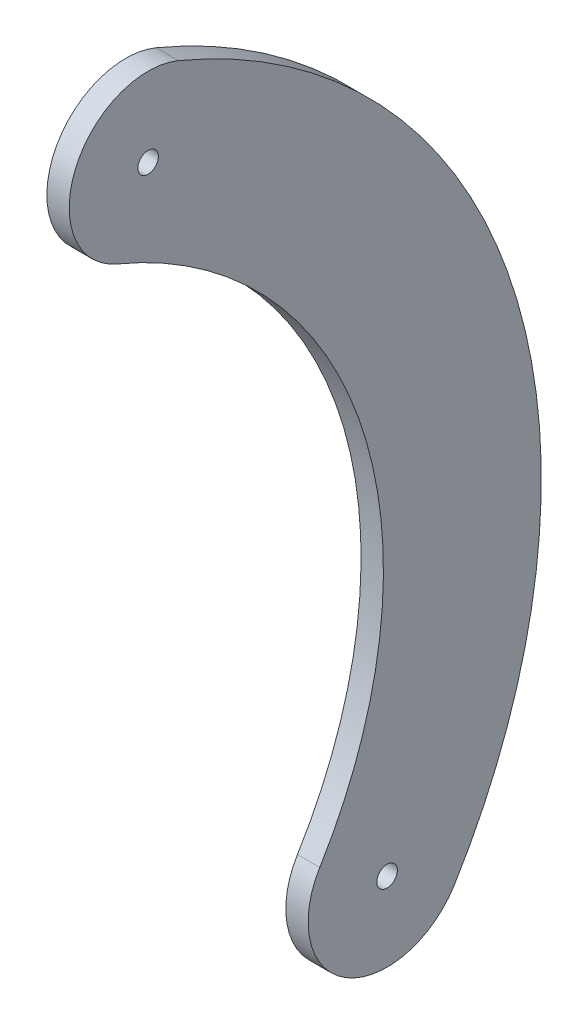
SolidWorks part; units mm, degrees
ref_plane "Front Plane" through (0, 0, 0) normal (0, 0, 1) x (1, 0, 0)
ref_plane "Top Plane" through (0, 0, 0) normal (0, 1, 0) x (1, 0, 0)
ref_plane "Right Plane" through (0, 0, 0) normal (1, 0, 0) x (0, 0, -1)
sketch "Sketch1" plane through (0, 0, 0) normal (1, 0, 0) x (0, 0, -1)
  line L0 (-85.3632, 0) -> (85.3632, 0) construction
  line L1 (0, 89.2233) -> (0, -89.2233) construction
  line L2 (-30.2742, 93.4694) -> (30.2742, -93.4694) construction
  line L3 (-11.2473, 99.6321) -> (49.301, -87.3068) construction
  line L4 (-49.301, 87.3068) -> (11.2473, -99.6321) construction
  line L5 (43.5935, 14.1196) -> (-43.5935, -14.1196) construction
  arc A0 (-11.2473, 99.6321) -> (-49.301, 87.3068) centre (-30.2742, 93.4694) ccw construction
  arc A1 (11.2473, -99.6321) -> (49.301, -87.3068) centre (30.2742, -93.4694) ccw construction
  circle A2 centre (-30.2742, 93.4694) radius 2.6067
  circle A3 centre (30.2742, -93.4694) radius 2.6067
  circle A4 centre (-30.2742, 93.4694) radius 20 construction
  circle A5 centre (30.2742, -93.4694) radius 20 construction
  arc A6 (-30.2742, 93.4694) -> (30.2742, -93.4694) centre (-79.9123, -25.8831) cw construction
  arc A7 (-30.2742, 93.4694) -> (30.2742, -93.4694) centre (-79.9123, -25.8831) cw construction
  arc A8 (47.3226, -103.9266) -> (-22.594, 111.936) centre (-79.9123, -25.8831) ccw
  arc A9 (13.2258, -83.0123) -> (-37.9543, 75.0029) centre (-79.9123, -25.8831) ccw
  arc A10 (13.2258, -83.0123) -> (47.3226, -103.9266) centre (30.2742, -93.4694) ccw
  arc A11 (-22.594, 111.936) -> (-37.9543, 75.0029) centre (-30.2742, 93.4694) ccw
  point P5 (0, 0)
  point P6 (0, 0)
  point P9 (0, 0)
  point P21 (0, 0)
  point P25 (43.0613, 13.9473)
  dimension "D1" = 196.5
  dimension "D3" = 5.2134
  dimension "D4" = 5.2134
  dimension "D2" = 40
extrude "Boss-Extrude1" add sketch "Sketch1" along normal blind 5.661
